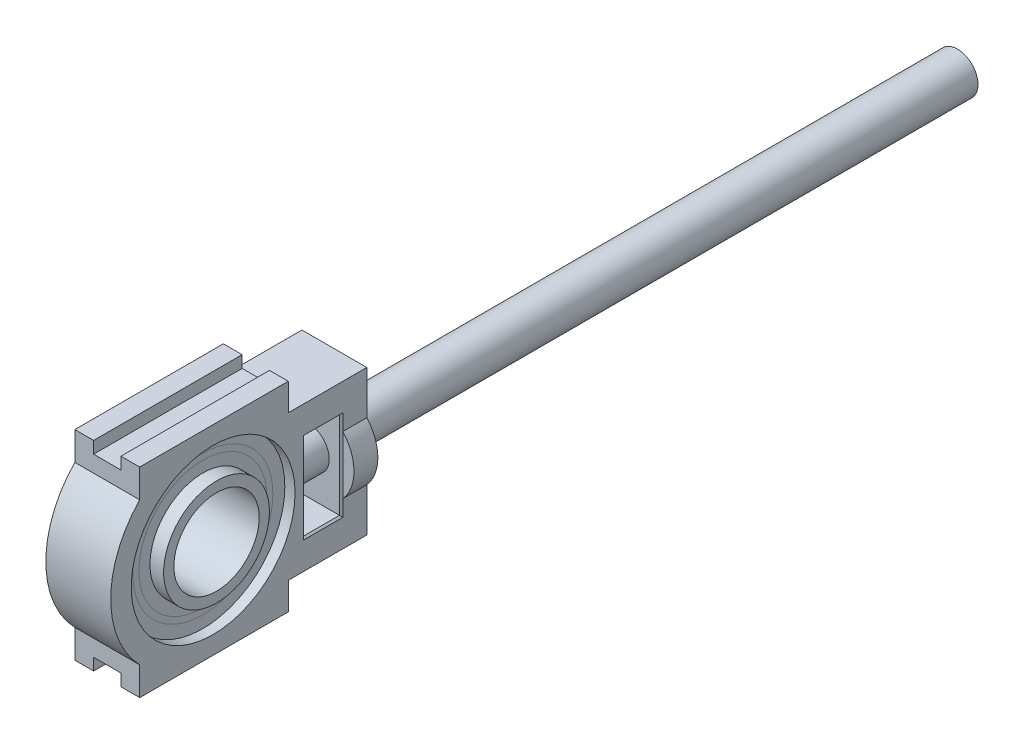
SolidWorks part; units mm, degrees
ref_plane "Front Plane" through (0, 0, 0) normal (0, 0, 1) x (1, 0, 0)
ref_plane "Top Plane" through (0, 0, 0) normal (0, 1, 0) x (1, 0, 0)
ref_plane "Right Plane" through (0, 0, 0) normal (1, 0, 0) x (0, 0, -1)
sketch "Sketch1" plane through (0, 0, 0) normal (1, 0, 0) x (0, 0, -1)
  line L0 (-43, 41.845) -> (-43, 58.5)
  line L1 (-43, 58.5) -> (44, 58.5)
  line L2 (44, 58.5) -> (44, 42.5)
  line L3 (44, 42.5) -> (90, 42.5)
  line L4 (90, 42.5) -> (90, -42.5)
  line L5 (0, 0) -> (75.3983, 0) construction
  line L6 (44, -42.5) -> (90, -42.5)
  line L7 (44, -58.5) -> (44, -42.5)
  line L8 (-43, -58.5) -> (44, -58.5)
  line L9 (-43, -41.845) -> (-43, -58.5)
  circle A0 centre (0, 0) radius 48
  arc A1 (-43, 41.845) -> (-43, -41.845) centre (0, 0) ccw
  point P10 (90, 0)
  dimension "D1" = 96
  dimension "D4" = 150
  dimension "D7" = 12
  dimension "D2" = 87
  dimension "D3" = 85
  dimension "D5" = 117
  dimension "D6" = 46
extrude "Boss-Extrude1" add sketch "Sketch1" along normal mid plane 38
sketch "Sketch2" plane through (0, 0, 0) normal (1, 0, 0) x (0, 0, -1)
  circle A0 centre (0, 0) radius 41
  circle A1 centre (0, 0) radius 37.5
  dimension "D1" = 82
  dimension "D2" = 3.5
extrude "Boss-Extrude2" add sketch "Sketch2" along normal offset from surface (13 mm away) 6 separate body up to face at (19, 0, -16.7)
sketch "Sketch3" plane through (0, 0, 0) normal (1, 0, 0) x (0, 0, -1)
  line L0 (90, -42.5) -> (90, 42.5) construction
  line L1 (54, -25.5) -> (75, -25.5)
  line L2 (54, -25.5) -> (54, 25.5)
  line L3 (54, 25.5) -> (75, 25.5)
  line L4 (75, -25.5) -> (75, 25.5)
  point P4 (54, 0)
  dimension "D1" = 21
  dimension "D2" = 51
  dimension "D3" = 15
extrude "Cut-Extrude1" cut sketch "Sketch3" against normal through all both and the other way through all
chamfer "Chamfer1" distance 1 angle 45 8 edges at (-19, 0, -54) (-19, 25.5, -64.5) (-19, 0, -75) (-19, -25.5, -64.5) (19, -25.5, -64.5) (19, 0, -75) (19, 25.5, -64.5) (19, 0, -54)
sketch "Sketch4" plane through (0, 0, -90) normal (0, 0, -1) x (-1, 0, 0)
  circle A0 centre (0, 0) radius 25.5
  dimension "D1" = 51
extrude "Boss-Extrude3" add sketch "Sketch4" against normal up to vertex (14 mm away)
sketch "Sketch5" plane through (0, 0, -90) normal (0, 0, -1) x (-1, 0, 0)
  circle A0 centre (0, 0) radius 12
  dimension "D1" = 24
extrude "Cut-Extrude2" cut sketch "Sketch5" against normal up to next (15 mm away)
sketch "Sketch6" plane through (0, 0, 0) normal (1, 0, 0) x (0, 0, -1)
  circle A0 centre (0, 0) radius 48 construction
  circle A1 centre (0, 0) radius 48
  circle A2 centre (0, 0) radius 41 construction
  circle A3 centre (0, 0) radius 41
extrude "Boss-Extrude4" add sketch "Sketch6" along normal offset from surface (13 mm away) 6 separate body up to face at (19, 0, -42.0556)
sketch "Sketch7" plane through (0, 0, 0) normal (1, 0, 0) x (0, 0, -1)
  circle A0 centre (0, 0) radius 31
  circle A1 centre (0, 0) radius 37.5 construction
  circle A2 centre (0, 0) radius 37.5
  dimension "D1" = 62
extrude "Boss-Extrude5" add sketch "Sketch7" along normal up to surface (13 mm away) separate body up to face at (13, 0, -37.5)
sketch "Sketch8" plane through (0, 0, 0) normal (1, 0, 0) x (0, 0, -1)
  circle A0 centre (0, 0) radius 25
  circle A1 centre (0, 0) radius 31 construction
  circle A2 centre (0, 0) radius 31
  dimension "D1" = 50
extrude "Boss-Extrude6" add sketch "Sketch8" along normal blind 21 and the other way blind 31 separate body
sketch "Sketch9" plane through (0, 0, 0) normal (0, 0, 1) x (1, 0, 0)
  line L0 (19, -58.5) -> (-19, -58.5) construction
  line L1 (8, -58.5) -> (-8, -58.5)
  line L2 (8, -58.5) -> (8, -51.5)
  line L3 (8, -51.5) -> (-8, -51.5)
  line L4 (-8, -58.5) -> (-8, -51.5)
  line L5 (0, 0) -> (-60.363, 0) construction
  line L6 (-8, 58.5) -> (-8, 51.5)
  line L7 (8, 51.5) -> (-8, 51.5)
  line L8 (8, 58.5) -> (8, 51.5)
  line L9 (8, 58.5) -> (-8, 58.5)
  point P13 (0, -51.5)
  dimension "D1" = 7
  dimension "D2" = 16
extrude "Cut-Extrude3" cut sketch "Sketch9" against normal through all both and the other way through all
mirror "Mirror1" about plane through (0, 0, 0) normal (1, 0, 0) of bodies 106 102 107
sketch "Sketch10" plane through (0, 0, -75) normal (0, 0, 1) x (1, 0, 0)
  circle A0 centre (0, 0) radius 12 construction
  circle A1 centre (0, 0) radius 12
extrude "Boss-Extrude7" add sketch "Sketch10" against normal blind 380 and the other way blind 20 separate body
